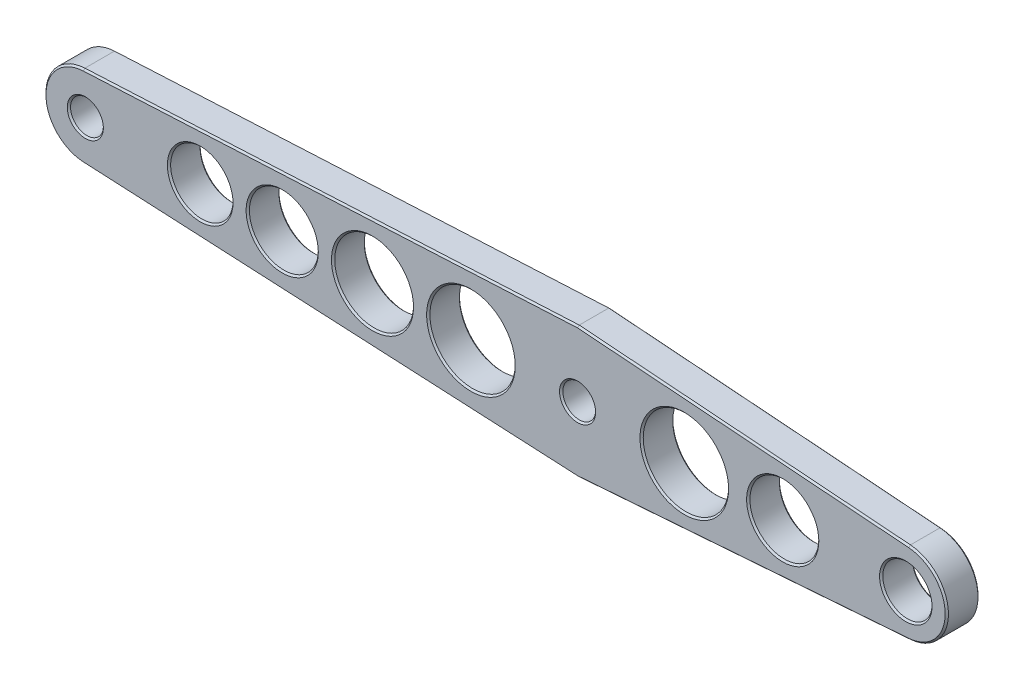
SolidWorks part; units mm, degrees
ref_plane "Front Plane" through (0, 0, 0) normal (0, 0, 1) x (1, 0, 0)
ref_plane "Top Plane" through (0, 0, 0) normal (0, 1, 0) x (1, 0, 0)
ref_plane "Right Plane" through (0, 0, 0) normal (1, 0, 0) x (0, 0, -1)
sketch "Sketch1" plane through (0, 0, 0) normal (0, 0, 1) x (1, 0, 0)
  line L0 (-30, 0) -> (-29, 0) construction
  line L1 (0, 0) -> (17.5, 0) construction
  line L2 (0, 0) -> (0, 4) construction
  line L3 (0, 0) -> (0, -4) construction
  line L4 (0, 4) -> (-30.1246, 2.4969)
  line L5 (0, -4) -> (-30.1246, -2.4969)
  line L6 (0, 4) -> (20.1861, 2.4931)
  line L7 (0, -4) -> (20.1861, -2.4931)
  line L8 (-27.5, 0) -> (0, 0) construction
  line L9 (18.5, 0) -> (20, 0) construction
  circle A0 centre (-30, 0) radius 1
  arc A1 (-30.1246, 2.4969) -> (-30.1246, -2.4969) centre (-30, 0) ccw
  circle A2 centre (0, 0) radius 1
  circle A3 centre (20, 0) radius 1.5
  arc A4 (20.1861, -2.4931) -> (20.1861, 2.4931) centre (20, 0) ccw
  circle A5 centre (6.5, 0) radius 2.6
  circle A6 centre (12.5, 0) radius 2.1
  circle A7 centre (-23, 0) radius 1.9
  circle A8 centre (-18, 0) radius 2.1
  circle A9 centre (-12.5, 0) radius 2.4
  circle A10 centre (-6.5, 0) radius 2.6
  dimension "D3" = 2
  dimension "D4" = 5
  dimension "D5" = 3.8
  dimension "D6" = 4.2
  dimension "D7" = 4.8
  dimension "D8" = 5.2
  dimension "D9" = 2
  dimension "D10" = 5.2
  dimension "D11" = 4.2
  dimension "D12" = 3
  dimension "D13" = 5
  dimension "D1" = 30
  dimension "D2" = 20
  dimension "D14" = 7
  dimension "D15" = 5
  dimension "D16" = 5.5
  dimension "D17" = 6
  dimension "D18" = 6
  dimension "D19" = 7.5
  dimension "D20" = 4
  dimension "D21" = 4
extrude "Boss-Extrude1" add sketch "Sketch1" along normal mid plane 2
chamfer "Chamfer1" distance 0.1 angle 45 30 edges at (-3.9, 0, -1) (-10.1, 0, -1) (-15.9, 0, -1) (-21.1, 0, -1) (14.6, 0, -1) (9.1, 0, -1) (21.5, 0, -1) (1, 0, -1) (-29, 0, -1) (-15.0623, 3.2484, -1) (-32.5, 0, -1) (-15.0623, -3.2484, -1) (10.0931, -3.2465, -1) (22.5, 0, -1) (10.0931, 3.2465, -1) (-3.9, 0, 1) (-15.9, 0, 1) (14.6, 0, 1) (21.5, 0, 1) (-29, 0, 1) (22.5, 0, 1) (10.0931, -3.2465, 1) (-15.0623, -3.2484, 1) (-32.5, 0, 1) (-15.0623, 3.2484, 1) (10.0931, 3.2465, 1) (1, 0, 1) (9.1, 0, 1) (-21.1, 0, 1) (-10.1, 0, 1)
